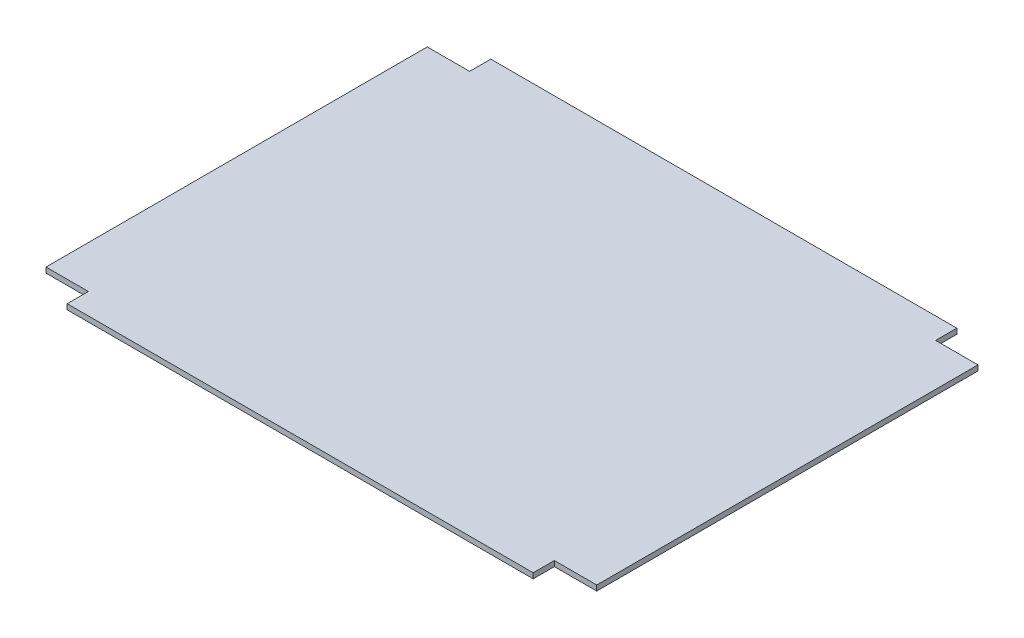
SolidWorks part; units mm, degrees
ref_plane "Front Plane" through (0, 0, 0) normal (0, 0, 1) x (1, 0, 0)
ref_plane "Top Plane" through (0, 0, 0) normal (0, 1, 0) x (1, 0, 0)
ref_plane "Right Plane" through (0, 0, 0) normal (1, 0, 0) x (0, 0, -1)
sketch "Sketch1" plane through (0, 0, 0) normal (0, 1, 0) x (1, 0, 0)
  line L0 (0, 0) -> (0, -400)
  line L1 (0, -400) -> (-440, -400)
  line L2 (-440, -400) -> (-440, -360)
  line L3 (-440, -360) -> (-520, -360)
  line L4 (-520, -360) -> (-520, 0)
  line L5 (-520, 0) -> (0, 0)
  dimension "D1" = 80
  dimension "D2" = 400
  dimension "D3" = 40
  dimension "D4" = 520
extrude "Boss-Extrude1" add sketch "Sketch1" along normal blind 10
mirror "Mirror1" about plane through (0, 0, 0) normal (0, 0, 1) of "Boss-Extrude1"
mirror "Mirror2" about plane through (0, 0, 0) normal (1, 0, 0) of "Mirror1", "Boss-Extrude1"
